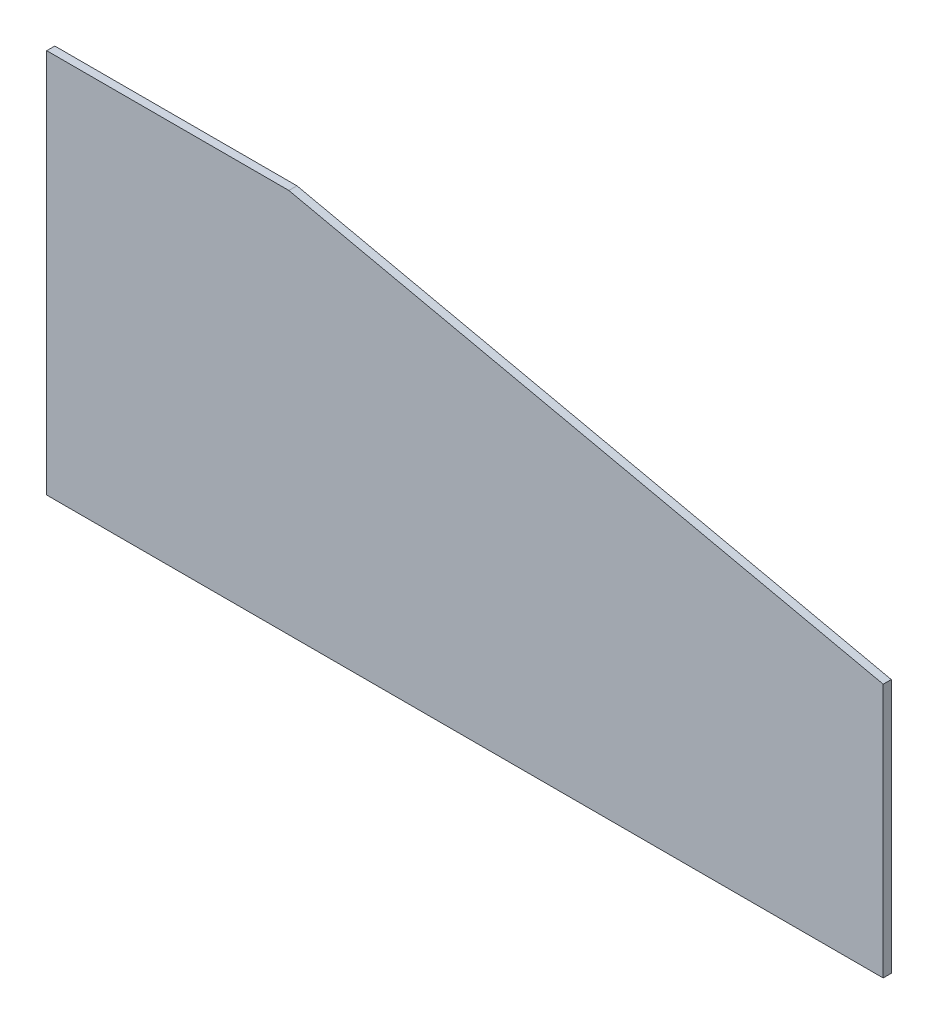
SolidWorks part; units mm, degrees
material "Pine"
ref_plane "Front Plane" through (0, 0, 0) normal (0, 0, 1) x (1, 0, 0)
ref_plane "Top Plane" through (0, 0, 0) normal (0, 1, 0) x (1, 0, 0)
ref_plane "Right Plane" through (0, 0, 0) normal (1, 0, 0) x (0, 0, -1)
sketch "Sketch1" plane through (0, 0, 0) normal (0, 0, 1) x (1, 0, 0)
  line L0 (0, 0) -> (0, 605)
  line L1 (0, 605) -> (380.6628, 605)
  line L2 (380.6628, 605) -> (1315, 400)
  line L3 (1315, 400) -> (1315, 0)
  line L4 (1315, 0) -> (0, 0)
  dimension "D1" = 90
  dimension "D2" = 77.625
  dimension "D3" = 400
  dimension "D4" = 1315
  dimension "D5" = 605
  dimension "D6" = 90
extrude "Boss-Extrude1" add sketch "Sketch1" along normal blind 12.7
